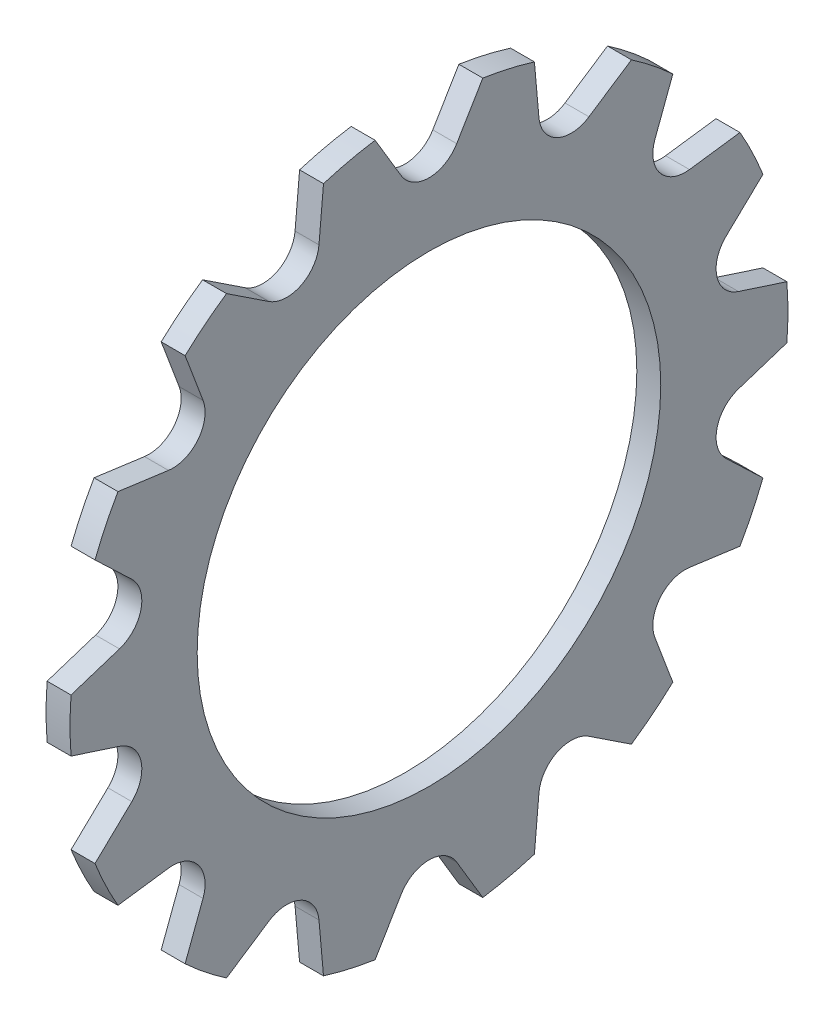
SolidWorks part; units mm, degrees
extrude "Base-Extrude" add sketch "Sketch1" against normal blind 1.6
sketch "Sketch1" plane through (0, 0, 0) normal (1, 0, 0) x (0, 0, -1)
  circle A0 centre (0, 0) radius 15.5
  circle A1 centre (0, 0) radius 24
  dimension "InsideDia" = 31
  dimension "OutsideDia" = 48
ref_plane "Plane1" through (0, 0, 0) normal (0, 0, 1) x (1, 0, 0)
ref_plane "Plane2" through (0, 0, 0) normal (0, 1, 0) x (1, 0, 0)
ref_plane "Plane3" through (0, 0, 0) normal (1, 0, 0) x (0, 0, -1)
sketch "Sketch3" plane through (0, 0, 0) normal (1, 0, 0) x (0, 0, -1)
  line L0 (1.855, 20.8034) -> (3.6, 23.7285)
  line L1 (-1.855, 20.8034) -> (-3.6, 23.7285)
  line L2 (-3.6, 23.7285) -> (-3.6, 25.8885)
  line L3 (-3.6, 25.8885) -> (3.6, 25.8885)
  line L4 (3.6, 25.8885) -> (3.6, 23.7285)
  arc A0 (-1.855, 20.8034) -> (1.855, 20.8034) centre (0, 21.91) ccw
  circle A1 centre (0, 0) radius 24 construction
  circle A2 centre (0, 0) radius 19.75 construction
  dimension "D1" = 4.32
  dimension "D4" = 39.5
  dimension "D2" = 7.2
  dimension "D3" = 2.16
  dimension "D5" = 3.6
extrude "TypeASlot" cut sketch "Sketch3" against normal through all
pattern_circular "TypeAPattern" count 14 over 360 about axis through (0, 0, 0) along (1, 0, 0) of "TypeASlot"
sketch "Sketch2" plane through (0, 0, 0) normal (1, 0, 0) x (0, 0, -1)
  line L0 (2.16, 0) -> (2.16, 17.59)
  line L1 (-2.16, 17.59) -> (-2.16, 0)
  line L2 (-2.16, 0) -> (2.16, 0)
  arc A0 (2.16, 17.59) -> (-2.16, 17.59) centre (0, 17.59) ccw
  circle A3 centre (0, 0) radius 19.75 construction
  dimension "D1" = 39.5
  dimension "SlotWidth" = 4.32
extrude "TypeJSlot" [suppressed] cut sketch "Sketch2" against normal through all
pattern_circular "TypeJPattern" [suppressed] count 14 over 360
equation "\"SlotWidth@Sketch2\" = \"OutsideDia@Sketch1\" * .09"
equation "\"D1@Sketch2\" = \"InsideDia@Sketch1\" +  ( \"OutsideDia@Sketch1\" - \"InsideDia@Sketch1\" )  / 2"
equation "\"D1@Sketch3\" = \"OutsideDia@Sketch1\" * .09"
equation "\"D2@Sketch3\" = \"OutsideDia@Sketch1\" * .15"
equation "\"D3@Sketch3\" = \"D1@Sketch3\" / 2"
equation "\"D4@Sketch3\" = \"InsideDia@Sketch1\" +  ( \"OutsideDia@Sketch1\" - \"InsideDia@Sketch1\" )  / 2"
equation "\"D5@Sketch3\" = \"D2@Sketch3\" / 2"
